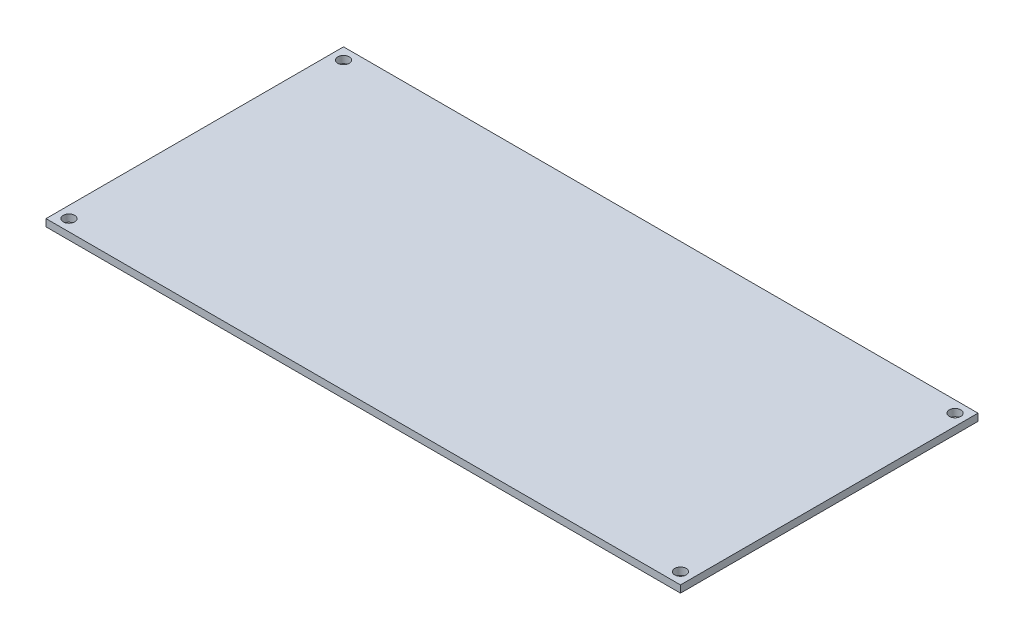
SolidWorks part; units mm, degrees
ref_plane "Plan de face" through (0, 0, 0) normal (0, 0, 1) x (1, 0, 0)
ref_plane "Plan de dessus" through (0, 0, 0) normal (0, 1, 0) x (1, 0, 0)
ref_plane "Plan de droite" through (0, 0, 0) normal (1, 0, 0) x (0, 0, -1)
sketch "Esquisse1" plane through (0, 0, 0) normal (0, 1, 0) x (1, 0, 0)
  line L1 (0, 0) -> (177, 0)
  line L2 (0, 0) -> (0, -83)
  line L3 (0, -83) -> (177, -83)
  line L4 (177, 0) -> (177, -83)
  dimension "D1" = 177
  dimension "D2" = 83
extrude "Boss.-Extru.1" add sketch "Esquisse1" along normal blind 2
sketch "Esquisse2" plane through (0, 2, 0) normal (0, 1, 0) x (1, 0, 0)
  line L0 (0, 0) -> (0, -83) construction
  line L1 (177, 0) -> (0, 0) construction
  circle A0 centre (3.2, -3.2) radius 1.6
  circle A1 centre (3.2, -79.8) radius 1.6
  circle A2 centre (173.8, -3.2) radius 1.6
  circle A3 centre (173.8, -79.8) radius 1.6
  dimension "D1" = 3.2
  dimension "D2" = 3.2
  dimension "D3" = 3.2
  dimension "D4" = 76.6
  dimension "D5" = 170.6
extrude "Enlèv. mat.-Extru.1" cut sketch "Esquisse2" against normal up to next
